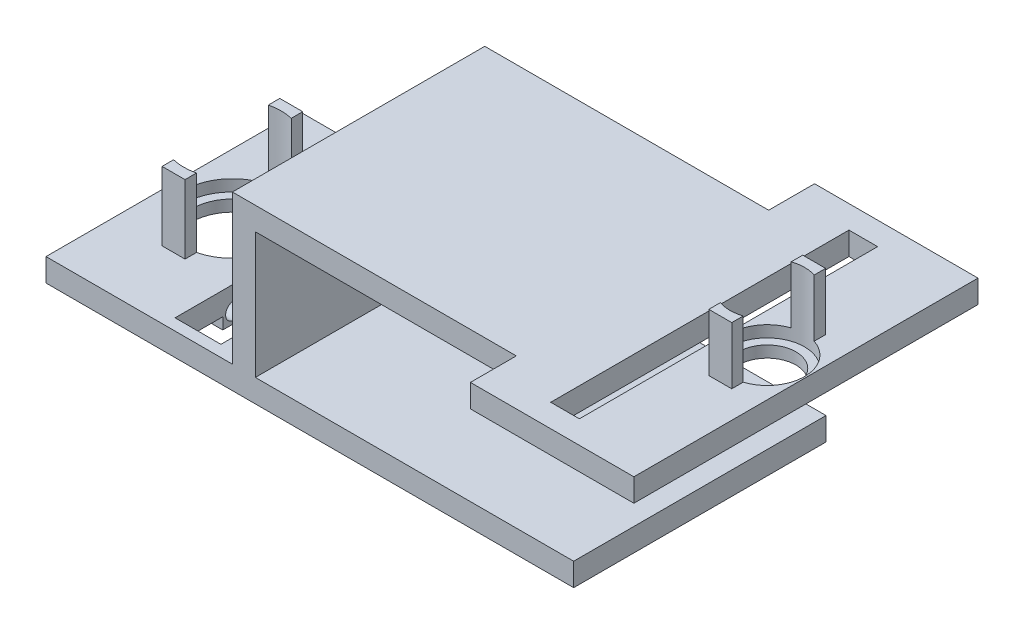
SolidWorks part; units mm, degrees
ref_plane "Front Plane" through (0, 0, 0) normal (0, 0, 1) x (1, 0, 0)
ref_plane "Top Plane" through (0, 0, 0) normal (0, 1, 0) x (1, 0, 0)
ref_plane "Right Plane" through (0, 0, 0) normal (1, 0, 0) x (0, 0, -1)
ref_plane "Plane1" through (0, 0, -11) normal (0, 0, 1) x (1, 0, 0)
sketch "Sketch1" plane through (0, 0, 0) normal (0, 0, 1) x (1, 0, 0)
  line L1 (23, -1) -> (-23, -1)
  line L2 (23, -1) -> (23, 1)
  line L3 (23, 1) -> (-23, 1)
  line L4 (-23, -1) -> (-23, 1)
  line L5 (23, -1) -> (-23, 1) construction
  line L6 (23, 1) -> (-23, -1) construction
  point P0 (0, 0)
  dimension "D1" = 2
  dimension "D2" = 46
extrude "Boss-Extrude1" add sketch "Sketch1" against normal blind 22
sketch "Sketch2" plane through (0, 1, 0) normal (0, 1, 0) x (1, 0, 0)
  line L0 (23, 0) -> (-23, 0) construction
  line L1 (-6.75, 0) -> (23, 0)
  line L2 (-6.75, 0) -> (-6.75, 22)
  line L3 (-6.75, 22) -> (23, 22)
  line L4 (23, 0) -> (23, 22)
  dimension "D1" = 29.75
extrude "Boss-Extrude2" add sketch "Sketch2" along normal blind 13
sketch "Sketch3" plane through (0, 0, 0) normal (0, 0, 1) x (1, 0, 0)
  line L0 (23, -1) -> (23, 14) construction
  line L1 (23, 12) -> (-4.75, 12)
  line L2 (23, 12) -> (23, 1)
  line L3 (23, 1) -> (-4.75, 1)
  line L4 (-4.75, 12) -> (-4.75, 1)
  line L5 (-6.75, 14) -> (23, 14) construction
  dimension "D1" = 2
  dimension "D2" = 11
  dimension "D3" = 27.75
extrude "Cut-Extrude1" cut sketch "Sketch3" against normal blind 22
sketch "Sketch4" plane through (0, 1, 0) normal (0, 1, 0) x (1, 0, 0)
  line L0 (-6.75, 0) -> (-23, 0) construction
  line L1 (-23, 22) -> (-23, 0) construction
  circle A0 centre (-17.75, 11) radius 4.25
  dimension "D3" = 8.5
  dimension "D1" = 11
  dimension "D2" = 5.25
extrude "Cut-Extrude2" cut sketch "Sketch4" against normal blind 1
sketch "Sketch5" plane through (0, 0, 0) normal (0, 1, 0) x (1, 0, 0)
  circle A0 centre (-17.75, 11) radius 3.5
  dimension "D1" = 7
extrude "Cut-Extrude3" cut sketch "Sketch5" against normal blind 1
sketch "Sketch16" plane through (0, 1, 0) normal (0, 1, 0) x (1, 0, 0)
  line L2 (-18.75, 6.8693) -> (-18.75, 5.8693)
  line L3 (-18.75, 5.8693) -> (-16.75, 5.8693)
  line L4 (-16.75, 6.8693) -> (-16.75, 5.8693)
  line L5 (-17.75, 6.75) -> (-16.75, 5.8693) construction
  line L6 (-18.75, 5.8693) -> (-17.75, 6.75) construction
  circle A0 centre (-17.75, 11) radius 4.25 construction
  arc A1 (-18.75, 6.8693) -> (-16.75, 6.8693) centre (-17.75, 11) ccw
  point P0 (-17.75, 6.75)
  dimension "2" = 2
  dimension "D2" = 1
  dimension "D3" = 1
extrude "Boss-Extrude4" add sketch "Sketch16" along normal blind 6 contours L2 L3 L4 A1
sketch "Sketch20" plane through (0, 1, 0) normal (0, 1, 0) x (1, 0, 0)
  line L0 (-6.75, 22) -> (-23, 22) construction
  line L1 (-15.75, 14.84) -> (-4.75, 14.84)
  line L2 (-15.75, 14.84) -> (-15.75, 16.84)
  line L3 (-15.75, 16.84) -> (-4.75, 16.84)
  line L4 (-4.75, 14.84) -> (-4.75, 16.84)
  line L6 (-4.75, 22) -> (-4.75, 0) construction
  point P7 (-4.75, 15.84)
  dimension "D2" = 2
  dimension "D3" = 11
  dimension "D5" = 6.16
extrude "Boss-Extrude8" add sketch "Sketch20" against normal blind 3 contours L3 L4 L1 L2
sketch "Sketch6" plane through (0, 1, 0) normal (0, 1, 0) x (1, 0, 0)
  line L0 (-6.75, 22) -> (-23, 22) construction
  line L1 (-12.75, 21) -> (-8.75, 21)
  line L2 (-12.75, 21) -> (-12.75, 1)
  line L3 (-12.75, 1) -> (-8.75, 1)
  line L4 (-8.75, 21) -> (-8.75, 1)
  line L5 (-6.75, 0) -> (-23, 0) construction
  line L6 (-6.75, 22) -> (-6.75, 0) construction
  dimension "D1" = 1
  dimension "D2" = 1
  dimension "D3" = 2
  dimension "D4" = 4
extrude "Cut-Extrude4" cut sketch "Sketch6" against normal through all contours L2 L3 L4 L1
sketch "Sketch25" plane through (-15.75, 0, 0) normal (-1, 0, 0) x (0, 0, 1)
  line L0 (-16.84, -2) -> (-14.84, -2)
  line L1 (-16.84, -2) -> (-16.84, -0.25)
  line L2 (-14.84, -2) -> (-14.84, -0.25)
  line L3 (-16.84, -0.25) -> (-14.84, -0.25)
  line L4 (-22, 1) -> (0, 1) construction
  dimension "D1" = 1.25
extrude "Cut-Extrude7" cut sketch "Sketch25" along normal through all
sketch "Sketch26" plane through (-15.75, 0, 0) normal (-1, 0, 0) x (0, 0, 1)
  line L0 (-14.84, -2) -> (-16.84, -2) construction
  line L1 (-22, 1) -> (-22, -1) construction
  circle A0 centre (-15.84, -1) radius 0.75
  dimension "D1" = 1.5
  dimension "D2" = 1
  dimension "D3" = 6.16
extrude "Cut-Extrude8" cut sketch "Sketch26" against normal blind 13
mirror "Mirror8" about plane through (0, 0, -11) normal (0, 0, 1) of "Cut-Extrude8", "Cut-Extrude7", "Cut-Extrude4", "Boss-Extrude8", "Boss-Extrude4"
sketch "Sketch12" plane through (0, 14, 0) normal (0, 1, 0) x (1, 0, 0)
  line L1 (23, 22) -> (18, 22)
  line L2 (23, 22) -> (23, 24)
  line L3 (32.25, 26) -> (18, 26)
  line L4 (18, 22) -> (18, 26)
  line L7 (23, 24) -> (25.5, 24)
  line L14 (25.5, 24) -> (25.5, 11)
  line L15 (25.5, 11) -> (32.25, 11)
  line L16 (32.25, 26) -> (32.25, 11)
  line L17 (-8.25, 11) -> (8.25, 11) construction
  dimension "D2" = 4
  dimension "D3" = 2
  dimension "D4" = 14.25
  dimension "D5" = 2.5
  dimension "D8" = 6.75
extrude "Boss-Extrude3" add sketch "Sketch12" against normal blind 2 contours L16 L15 L14 L7 L2 L1 L4 L3
sketch "Sketch13" plane through (0, 14, 0) normal (0, 1, 0) x (1, 0, 0)
  line L1 (32.25, 26) -> (32.25, 11) construction
  line L2 (-8.25, 11) -> (8.25, 11) construction
  circle A0 centre (28.875, 11) radius 3.25
  dimension "D3" = 6.5
  dimension "D2" = 3.375
extrude "Cut-Extrude5" cut sketch "Sketch13" against normal blind 1
sketch "Sketch14" plane through (0, 13, 0) normal (0, 1, 0) x (1, 0, 0)
  circle A0 centre (28.875, 11) radius 2.5
  dimension "D1" = 5
extrude "Cut-Extrude6" cut sketch "Sketch14" against normal blind 1
sketch "Sketch18" plane through (0, 14, 0) normal (0, 1, 0) x (1, 0, 0)
  line L2 (29.875, 14.0923) -> (29.875, 15.0923)
  line L3 (29.875, 15.0923) -> (27.875, 15.0923)
  line L4 (27.875, 14.0923) -> (27.875, 15.0923)
  line L5 (28.875, 14.25) -> (27.875, 15.0923) construction
  line L6 (29.875, 15.0923) -> (28.875, 14.25) construction
  circle A0 centre (28.875, 11) radius 3.25 construction
  arc A1 (29.875, 14.0923) -> (27.875, 14.0923) centre (28.875, 11) ccw
  point P0 (28.875, 14.25)
  dimension "2" = 2
  dimension "D2" = 1
  dimension "D3" = 1
extrude "Boss-Extrude6" add sketch "Sketch18" along normal blind 5 contours L4 L3 L2 A1
mirror "Mirror3" about plane through (0, 0, -11) normal (0, 0, 1) of "Boss-Extrude6", "Cut-Extrude6", "Cut-Extrude5", "Boss-Extrude3"
